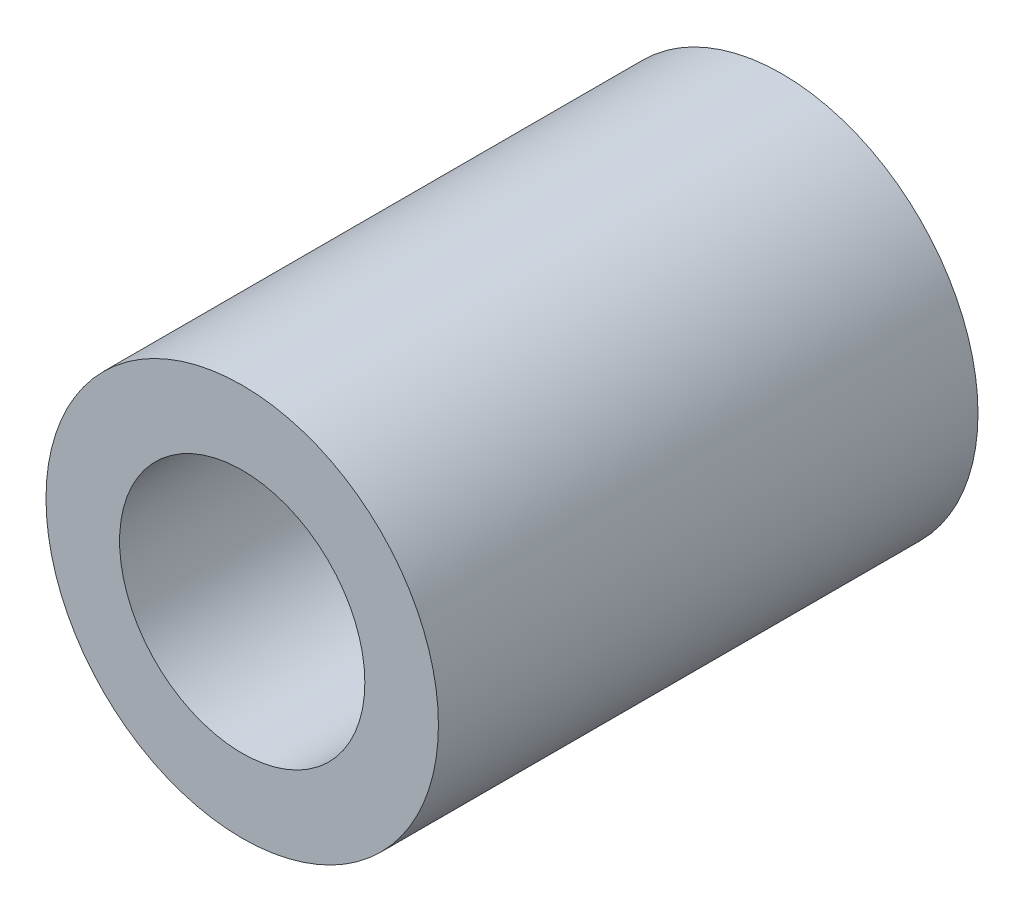
SolidWorks part; units mm, degrees
material "Plain Carbon Steel"
ref_plane "Front Plane" through (0, 0, 0) normal (0, 0, 1) x (1, 0, 0)
ref_plane "Top Plane" through (0, 0, 0) normal (0, 1, 0) x (1, 0, 0)
ref_plane "Right Plane" through (0, 0, 0) normal (1, 0, 0) x (0, 0, -1)
sketch "Sketch1" plane through (0, 0, 0) normal (0, 0, 1) x (1, 0, 0)
  circle A0 centre (0, 0) radius 5
  circle A1 centre (0, 0) radius 8
  dimension "D1" = 10
  dimension "D2" = 16
extrude "Boss-Extrude1" add sketch "Sketch1" along normal mid plane 22
